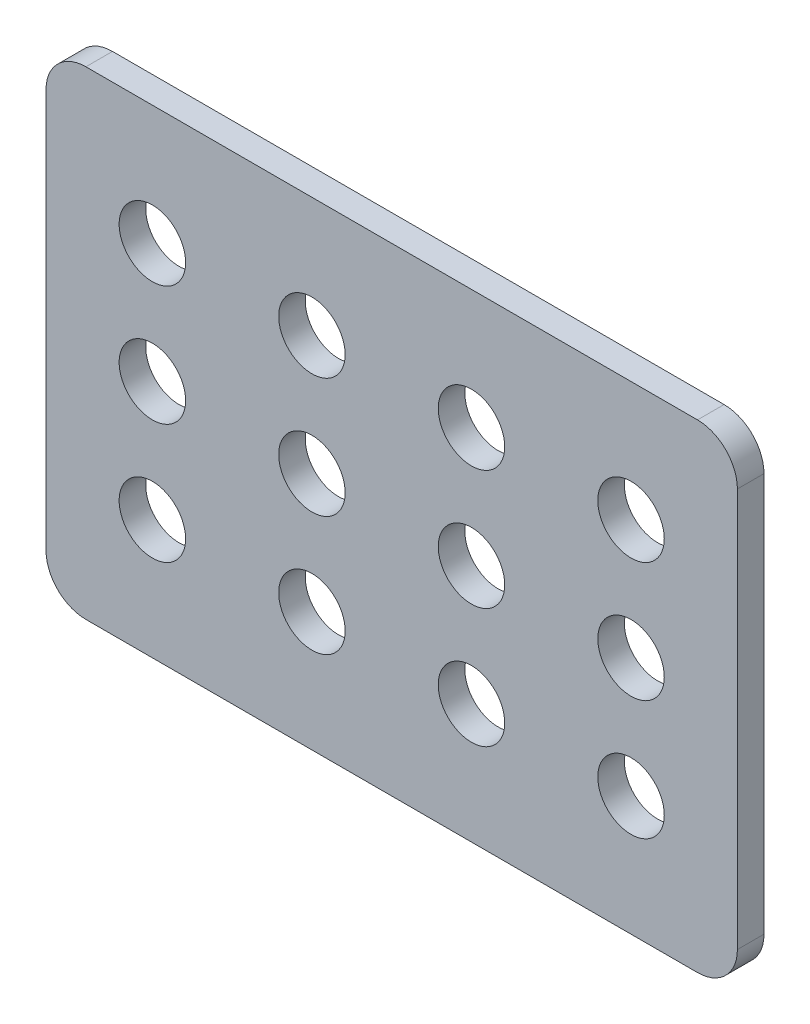
SolidWorks part; units mm, degrees
ref_plane "Płaszczyzna przednia" through (0, 0, 0) normal (0, 0, 1) x (1, 0, 0)
ref_plane "Płaszczyzna górna" through (0, 0, 0) normal (0, 1, 0) x (1, 0, 0)
ref_plane "Płaszczyzna prawa" through (0, 0, 0) normal (1, 0, 0) x (0, 0, -1)
sketch "Szkic1" plane through (0, 0, 0) normal (0, 0, 1) x (1, 0, 0)
  line L1 (15, 0) -> (245, 0)
  line L2 (0, 15) -> (0, 165)
  line L3 (15, 180) -> (245, 180)
  line L4 (260, 15) -> (260, 165)
  circle A0 centre (40, 45) radius 12.5
  circle A1 centre (100, 45) radius 12.5
  circle A2 centre (160, 45) radius 12.5
  circle A3 centre (220, 45) radius 12.5
  circle A4 centre (100, 90) radius 12.5
  circle A5 centre (160, 90) radius 12.5
  circle A6 centre (220, 90) radius 12.5
  circle A7 centre (100, 135) radius 12.5
  circle A8 centre (160, 135) radius 12.5
  circle A9 centre (220, 135) radius 12.5
  circle A10 centre (40, 90) radius 12.5
  circle A11 centre (40, 135) radius 12.5
  arc A12 (245, 0) -> (260, 15) centre (245, 15) ccw
  arc A13 (260, 165) -> (245, 180) centre (245, 165) ccw
  arc A14 (15, 180) -> (0, 165) centre (15, 165) ccw
  arc A15 (15, 0) -> (0, 15) centre (15, 15) cw
  point P7 (0, 0)
  point P8 (0, 0)
  point P9 (0, 0)
  point P32 (0, 0)
  point P33 (0, 0)
  point P34 (0, 0)
  point P37 (260, 0)
  point P42 (0, 180)
  point P45 (0, 0)
  point P46 (0, 0)
  dimension "D3" = 25
  dimension "D11" = 15
  dimension "D1" = 180
  dimension "D2" = 260
  dimension "D4" = 45
  dimension "D5" = 40
  dimension "D8" = 60
  dimension "D10" = 45
  dimension "D6" = 4
  dimension "D7" = 3
extrude "Dodanie-wyciągnięcie1" add sketch "Szkic1" along normal blind 10
